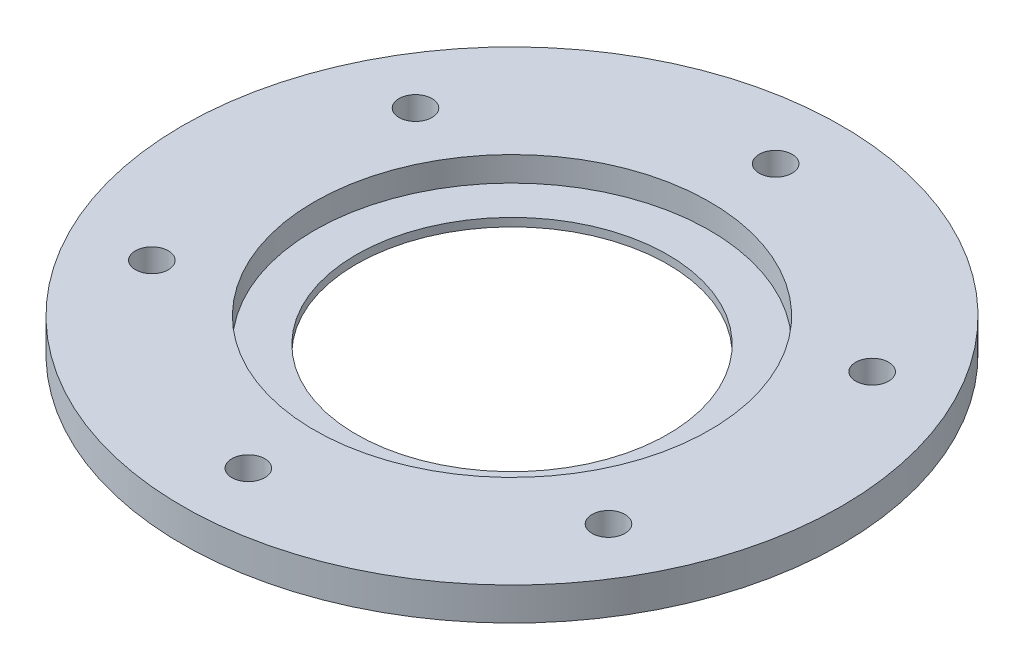
SolidWorks part; units mm, degrees
ref_plane "前基準面" through (0, 0, 0) normal (0, 0, 1) x (1, 0, 0)
ref_plane "上基準面" through (0, 0, 0) normal (0, 1, 0) x (1, 0, 0)
ref_plane "右基準面" through (0, 0, 0) normal (1, 0, 0) x (0, 0, -1)
sketch "草圖4" plane through (0, 0, 0) normal (0, 0, 1) x (1, 0, 0)
  line L5 (120, 20) -> (120, 5)
  line L8 (120, 20) -> (200, 20)
  line L9 (200, 20) -> (200, 0)
  line L10 (0, 45.9804) -> (0, -64.3554) construction
  line L11 (200, 0) -> (94.5, 0)
  line L12 (94.5, 0) -> (94.5, 5)
  line L13 (94.5, 5) -> (120, 5)
  dimension "D1" = 200
  dimension "D2" = 20
  dimension "D3" = 80
  dimension "D4" = 25.5
  dimension "D5" = 5
revolve "旋轉1" add sketch "草圖4" angle 360 about L10
sketch "草圖5" plane through (0, 20, 0) normal (0, 1, 0) x (1, 0, 0)
  line L0 (0, 238.7457) -> (0, -247.0444) construction
  line L1 (-254.0663, 0) -> (441.105, 0) construction
  circle A0 centre (0, 160) radius 10
  circle A1 centre (138.5641, 80) radius 10
  circle A2 centre (138.5641, -80) radius 10
  circle A3 centre (0, -160) radius 10
  circle A4 centre (-138.5641, -80) radius 10
  circle A5 centre (-138.5641, 80) radius 10
  point P19 (0, 0)
  dimension "D1" = 160
  dimension "D2" = 20
  dimension "D3" = 6
extrude "除料-伸長1" cut sketch "草圖5" against normal up to next
